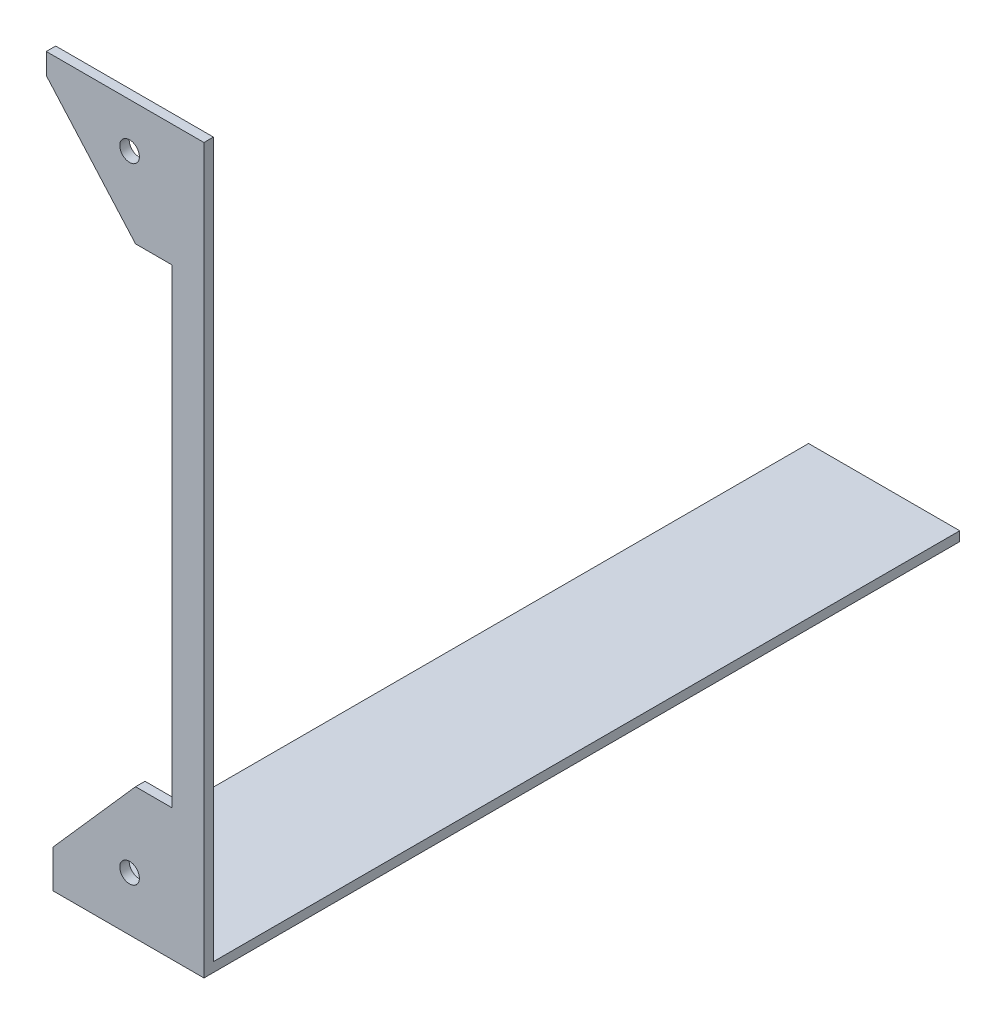
SolidWorks part; units mm, degrees
ref_plane "Front Plane" through (0, 0, 0) normal (0, 0, 1) x (1, 0, 0)
ref_plane "Top Plane" through (0, 0, 0) normal (0, 1, 0) x (1, 0, 0)
ref_plane "Right Plane" through (0, 0, 0) normal (1, 0, 0) x (0, 0, -1)
sketch "Sketch1" plane through (0, 0, 0) normal (0, 0, 1) x (1, 0, 0)
  line L0 (-250, 120) -> (0, 120) construction
  line L1 (0, 118) -> (0, 2) construction
  line L2 (0, 0) -> (-250, 0) construction
  line L3 (-26.5, 116.5) -> (-11.5, 99.5) construction
  line L4 (-11.5, 99.5) -> (-5.4, 99.5) construction
  line L5 (-5.4, 99.5) -> (-5.4, 20.5) construction
  line L6 (-11.5, 20.5) -> (-26.5, 3.5) construction
  line L7 (-5.4, 20.5) -> (-11.5, 20.5) construction
  line L8 (-26.5, 120) -> (0, 120)
  line L9 (0, 120) -> (0, 0)
  line L10 (0, 0) -> (-26.5, 0)
  line L11 (-26.5, 116.5) -> (-11.5, 99.5)
  line L12 (-11.5, 99.5) -> (-5.4, 99.5)
  line L13 (-5.4, 99.5) -> (-5.4, 20.5)
  line L14 (-11.5, 20.5) -> (-26.5, 3.5)
  line L15 (-5.4, 20.5) -> (-11.5, 20.5)
  line L16 (-26.5, 3.5) -> (-26.5, 0)
  line L17 (-26.5, 116.5) -> (-26.5, 120)
  line L18 (-25.4, 4.7467) -> (-25.4, 0)
  arc A0 (-14.15, 112.5) -> (-10.85, 112.5) centre (-12.5, 112.5) ccw construction
  arc A1 (-10.85, 112.5) -> (-14.15, 112.5) centre (-12.5, 112.5) ccw construction
  arc A2 (-14.15, 7.5) -> (-10.85, 7.5) centre (-12.5, 7.5) ccw construction
  arc A3 (-10.85, 7.5) -> (-14.15, 7.5) centre (-12.5, 7.5) ccw construction
  arc A4 (-14.15, 112.5) -> (-10.85, 112.5) centre (-12.5, 112.5) ccw
  arc A5 (-10.85, 112.5) -> (-14.15, 112.5) centre (-12.5, 112.5) ccw
  arc A6 (-14.15, 7.5) -> (-10.85, 7.5) centre (-12.5, 7.5) ccw
  arc A7 (-10.85, 7.5) -> (-14.15, 7.5) centre (-12.5, 7.5) ccw
  dimension "D1" = 25.4
extrude "Boss-Extrude1" add sketch "Sketch1" along normal blind 1.5875 contours L14 L18 L10 L9 L8 L17 L11 L12 L13 L15 A7 A6 A5 A4
sketch "Sketch2" plane through (0, 0, 0) normal (0, 1, 0) x (1, 0, 0)
  line L0 (0, -1.5875) -> (0, 125.4125)
  line L1 (0, 125.4125) -> (-25.4, 125.4125)
  line L2 (-25.4, 125.4125) -> (-25.4, -1.5875)
  line L4 (0, -1.5875) -> (-25.4, -1.5875) construction
  line L5 (0, -1.5875) -> (-25.4, -1.5875)
  point P4 (0, 0)
  point P8 (0, 0)
  point P9 (-25.7909, -1.5875)
  dimension "D1" = 127
extrude "Boss-Extrude2" add sketch "Sketch2" against normal blind 1.5875
